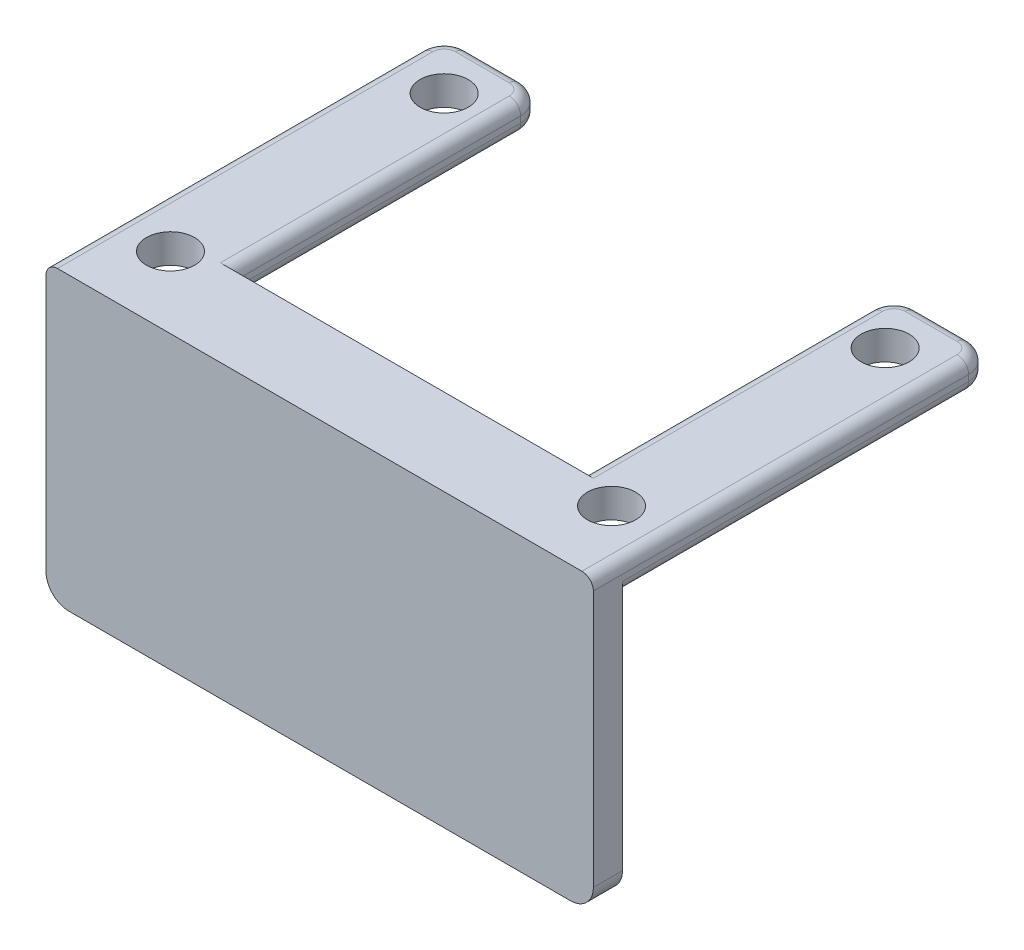
SolidWorks part; units mm, degrees
material "ABS"
ref_plane "X-Y Datum" through (0, 0, 0) normal (0, 0, 1) x (1, 0, 0)
ref_plane "X-Z Datum" through (0, 0, 0) normal (0, 1, 0) x (1, 0, 0)
ref_plane "Y-Z Datum" through (0, 0, 0) normal (1, 0, 0) x (0, 0, -1)
sketch "Sketch1" plane through (0, 0, 0) normal (0, 1, 0) x (1, 0, 0)
  line L4 (-28.418, 1.935) -> (2.142, 1.935)
  line L5 (-34.5577, 24.5037) -> (-37.0977, 24.5037) construction
  line L6 (8.1233, 24.5037) -> (10.6633, 24.5037) construction
  line L7 (-32.4577, 26.6037) -> (-32.4577, 29.1437) construction
  line L15 (-37.0977, 29.1437) -> (-28.418, 29.1437)
  line L16 (-37.0977, 29.1437) -> (-37.0977, -3.0553)
  line L17 (-37.0977, -3.0553) -> (-28.5207, -3.0553)
  line L18 (-28.418, 29.1437) -> (-28.418, 1.935)
  line L19 (10.6633, 29.1437) -> (2.142, 29.1437)
  line L20 (10.6633, 29.1437) -> (10.6633, -3.0553)
  line L21 (10.6633, -3.0553) -> (2.0863, -3.0553)
  line L22 (2.142, 29.1437) -> (2.142, 1.935)
  line L23 (-28.5207, -3.0553) -> (2.0863, -3.0553)
  line L25 (6.0233, 26.6037) -> (6.0233, 29.1437) construction
  circle A4 centre (-32.4577, 24.5037) radius 2.1
  circle A5 centre (-32.4577, 0.6277) radius 2.1
  circle A6 centre (6.0233, 24.5037) radius 2.1
  circle A7 centre (6.0233, 0.6277) radius 2.1
  point P10 (-28.418, 29.1437)
  point P11 (2.142, 29.1437)
extrude "Boss-Extrude1" add sketch "Sketch1" along normal blind 2.54
sketch "Sketch2" plane through (0, 2.54, 0) normal (0, -1, 0) x (1, 0, 0)
  line L0 (10.6633, 3.0553) -> (10.6633, -29.1437) construction
  line L5 (-37.0977, 3.0553) -> (10.6633, 3.0553)
  line L6 (-37.0977, 3.0553) -> (-37.0977, 5.5953)
  line L7 (-37.0977, 5.5953) -> (10.6633, 5.5953)
  line L8 (10.6633, 3.0553) -> (10.6633, 5.5953)
  line L9 (-37.0977, 3.0553) -> (10.6633, 3.0553) construction
  point P0 (10.6633, 3.0553)
extrude "Boss-Extrude2" add sketch "Sketch2" along normal blind 25.4
fillet "Fillet1" radius 2 6 edges at (-28.418, 1.27, -29.1437) (-37.0977, 1.27, -29.1437) (-37.0977, -22.86, 4.3253) (10.6633, -22.86, 4.3253) (2.142, 1.27, -29.1437) (10.6633, 1.27, -29.1437)
fillet "Fillet2" radius 1 20 edges at (-37.0977, 0, -12.0442) (-36.5119, 0, -28.5579) (-32.7579, 0, -29.1437) (-29.0038, 0, -28.5579) (10.6633, 0, -12.0442) (10.0775, 0, -28.5579) (6.4026, 0, -29.1437) (2.7278, 0, -28.5579) (2.142, 2.54, -14.5394) (2.7278, 2.54, -28.5579) (6.4026, 2.54, -29.1437) (10.0775, 2.54, -28.5579) (-28.418, 2.54, -14.5394) (-29.0038, 2.54, -28.5579) (-32.7579, 2.54, -29.1437) (-36.5119, 2.54, -28.5579) (-28.418, 0, -14.5394) (2.142, 0, -14.5394) (10.6633, 2.54, -10.7742) (-37.0977, 2.54, -10.7742)
